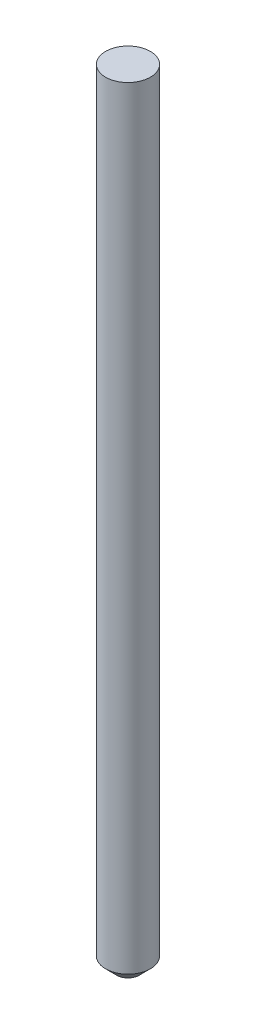
SolidWorks part; units mm, degrees
ref_plane "Front Plane" through (0, 0, 0) normal (0, 0, 1) x (1, 0, 0)
ref_plane "Top Plane" through (0, 0, 0) normal (0, 1, 0) x (1, 0, 0)
ref_plane "Right Plane" through (0, 0, 0) normal (1, 0, 0) x (0, 0, -1)
sketch "Sketch1" plane through (0, 0, 0) normal (0, 1, 0) x (1, 0, 0)
  circle A0 centre (0, 0) radius 4
  dimension "D1" = 8
extrude "Boss-Extrude1" add sketch "Sketch1" along normal blind 140
chamfer "Chamfer1" distance 2 angle 45 1 edges at (0, 0, 4)
sketch "Sketch3" plane through (0, 0, 0) normal (1, 0, 0) x (0, 0, -1)
  circle A0 centre (0, 0) radius 1.25
  dimension "D1" = 2.5
